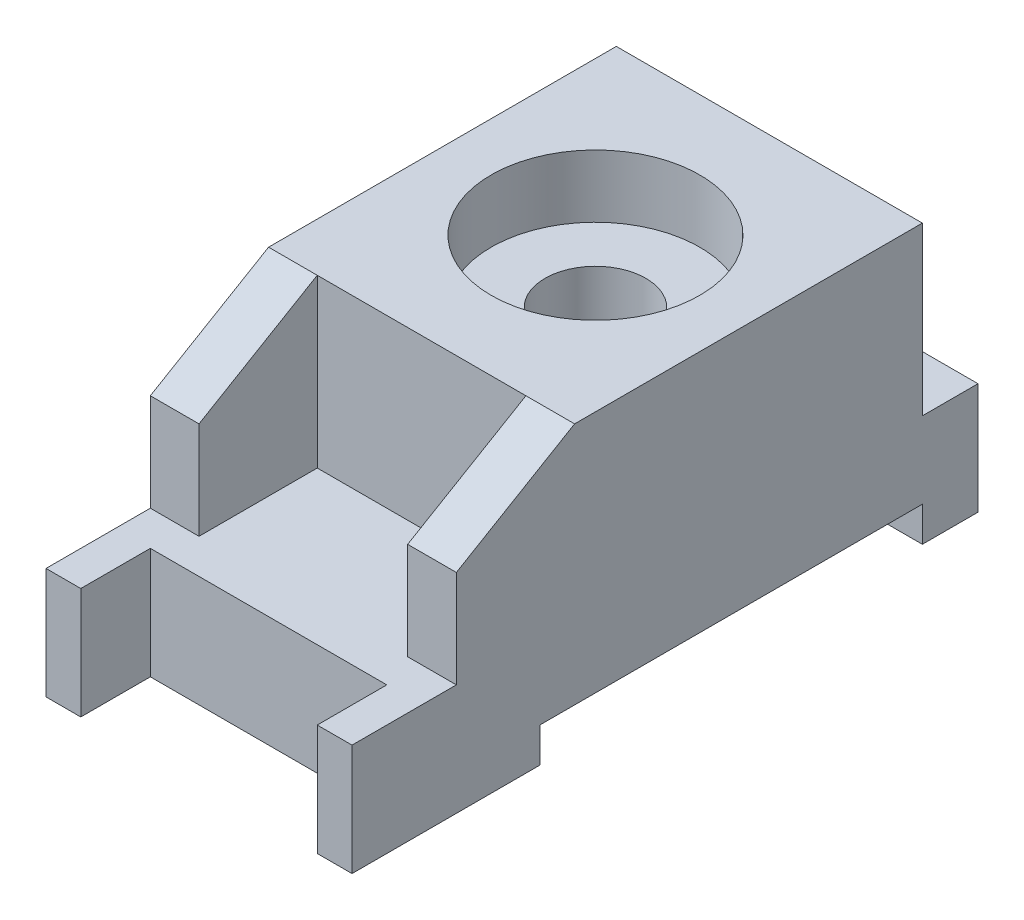
SolidWorks part; units mm, degrees
ref_plane "Спереди" through (0, 0, 0) normal (0, 0, 1) x (1, 0, 0)
ref_plane "Сверху" through (0, 0, 0) normal (0, 1, 0) x (1, 0, 0)
ref_plane "Справа" through (0, 0, 0) normal (1, 0, 0) x (0, 0, -1)
sketch "Эскиз1" plane through (0, 0, 0) normal (0, 0, 1) x (1, 0, 0)
  line L1 (-22, -8) -> (22, -8)
  line L2 (-22, -8) -> (-22, 8)
  line L3 (-22, 8) -> (22, 8)
  line L4 (22, -8) -> (22, 8)
  line L5 (-22, -8) -> (22, 8) construction
  line L6 (-22, 8) -> (22, -8) construction
  point P0 (0, 0)
  dimension "D1" = 44
  dimension "D2" = 16
extrude "Бобышка-Вытянуть1" add sketch "Эскиз1" along normal blind 90
sketch "Эскиз2" plane through (22, 0, 0) normal (1, 0, 0) x (0, 0, -1)
  line L0 (-8, -8) -> (-63, -8)
  line L1 (-90, -8) -> (0, -8) construction
  line L2 (-63, -8) -> (-63, -3)
  line L3 (-63, -3) -> (-8, -3)
  line L4 (-8, -3) -> (-8, -8)
  dimension "D1" = 8
  dimension "D2" = 55
  dimension "D3" = 5
extrude "Вырез-Вытянуть1" cut sketch "Эскиз2" against normal through all
sketch "Эскиз3" plane through (0, 8, 0) normal (0, 1, 0) x (1, 0, 0)
  line L0 (-17, -90) -> (-17, -80)
  line L1 (22, -90) -> (-22, -90) construction
  line L2 (-17, -80) -> (17, -80)
  line L3 (17, -80) -> (17, -90)
  line L4 (17, -90) -> (-17, -90)
  dimension "D1" = 34
  dimension "D2" = 5
  dimension "D3" = 10
extrude "Вырез-Вытянуть2" cut sketch "Эскиз3" against normal through all
sketch "Эскиз4" plane through (0, 8, 0) normal (0, 1, 0) x (1, 0, 0)
  line L0 (-22, -75) -> (22, -75)
  line L1 (-22, -90) -> (-22, 0) construction
  line L2 (22, -90) -> (22, 0) construction
  line L3 (22, -75) -> (22, -8)
  line L4 (22, -8) -> (-22, -8)
  line L5 (-22, -8) -> (-22, -75)
  dimension "D1" = 15
  dimension "D2" = 8
extrude "Бобышка-Вытянуть2" add sketch "Эскиз4" along normal blind 24
sketch "Эскиз5" plane through (0, 32, 0) normal (0, 1, 0) x (1, 0, 0)
  line L0 (-15, -75) -> (-15, -58)
  line L1 (-22, -75) -> (22, -75) construction
  line L2 (-15, -58) -> (15, -58)
  line L3 (15, -58) -> (15, -75)
  line L4 (-22, -75) -> (22, -75) construction
  line L5 (15, -75) -> (-15, -75)
  line L6 (22, -8) -> (-22, -8) construction
  dimension "D1" = 30
  dimension "D2" = 7
  dimension "D3" = 50
extrude "Вырез-Вытянуть3" cut sketch "Эскиз5" against normal blind 24
sketch "Эскиз6" plane through (22, 0, 0) normal (1, 0, 0) x (0, 0, -1)
  line L0 (-75, 22) -> (-58, 32)
  line L1 (-75, 32) -> (-75, 8) construction
  line L2 (-75, 32) -> (-8, 32) construction
  line L3 (-75, 22) -> (-75, 32)
  line L4 (-75, 32) -> (-58, 32)
  dimension "D1" = 14
  dimension "D2" = 50
extrude "Вырез-Вытянуть4" cut sketch "Эскиз6" against normal through all
sketch "Эскиз7" plane through (0, 32, 0) normal (0, 1, 0) x (1, 0, 0)
  line L0 (22, -8) -> (-22, -8) construction
  circle A0 centre (0, -33) radius 15
  dimension "D2" = 30
  dimension "D1" = 25
extrude "Вырез-Вытянуть5" cut sketch "Эскиз7" against normal blind 9
sketch "Эскиз8" plane through (0, 23, 0) normal (0, 1, 0) x (1, 0, 0)
  circle A0 centre (0, -33) radius 7.25
  dimension "D1" = 14.5
extrude "Вырез-Вытянуть6" cut sketch "Эскиз8" against normal through all
